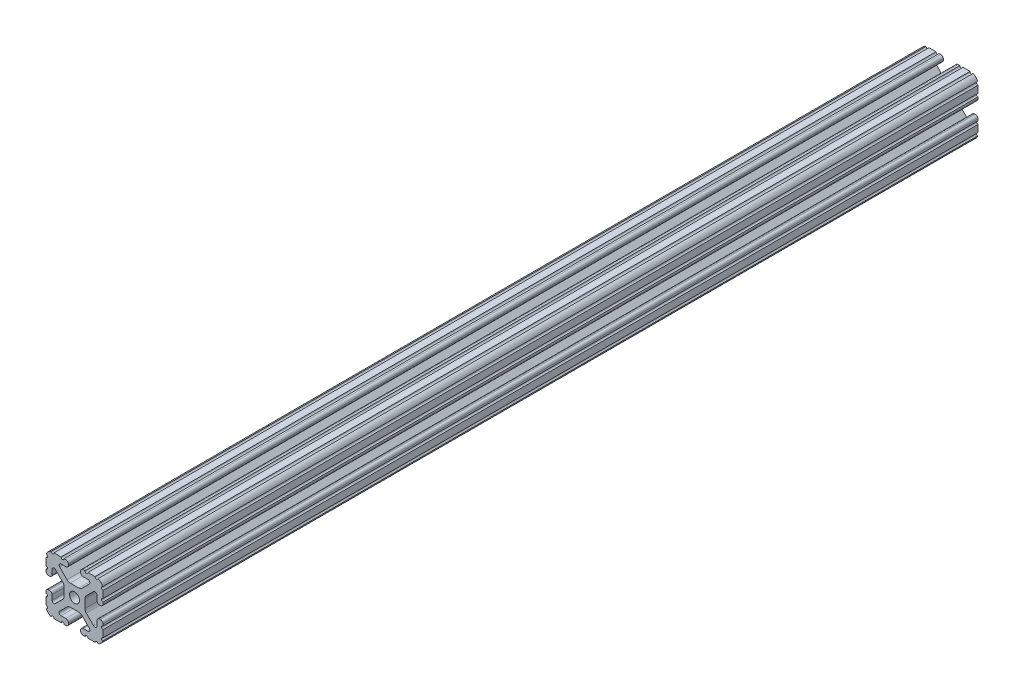
SolidWorks part; units mm, degrees
ref_plane "Front Plane" through (0, 0, 0) normal (0, 0, 1) x (1, 0, 0)
ref_plane "Top Plane" through (0, 0, 0) normal (0, 1, 0) x (1, 0, 0)
ref_plane "Right Plane" through (0, 0, 0) normal (1, 0, 0) x (0, 0, -1)
sketch "Sketch2" plane through (0, 0, 0) normal (0, 0, 1) x (1, 0, 0)
  line L0 (0, 19.05) -> (0, -19.05) construction
  line L1 (-19.05, 0) -> (19.05, 0) construction
  line L2 (4.064, -19.05) -> (19.05, -19.05)
  line L3 (19.05, -19.05) -> (19.05, -4.064)
  line L4 (4.064, -19.05) -> (4.064, -14.986)
  line L5 (4.064, -14.986) -> (12.1123, -14.986)
  line L6 (12.1123, -14.986) -> (4.1113, -6.985)
  line L7 (0, 0) -> (19.05, -19.05) construction
  line L8 (19.05, -4.064) -> (14.986, -4.064)
  line L9 (14.986, -4.064) -> (14.986, -12.1123)
  line L10 (14.986, -12.1123) -> (6.985, -4.1113)
  circle A0 centre (0, 0) radius 3.3274
  arc A1 (8.9963, -14.986) -> (9.909, -12.7826) centre (8.9963, -13.6953) ccw construction
  point P8 (0, -6.985)
  dimension "Center Hole Diameter" = 6.6548
  dimension "Rail Height" = 38.1
  dimension "Rail Width" = 38.1
  dimension "T-Slot Width" = 8.128
  dimension "Slot Inner Width" = 20.574
  dimension "Thickness" = 4.064
  dimension "Slot Depth" = 8.001
  dimension "D1" = 4.064
sketch "Sketch3" plane through (0, 0, 0) normal (1, 0, 0) x (0, 0, -1)
  line L0 (-292.5, -19.05) -> (292.5, -19.05) construction
  line L1 (-267.1, 0) -> (267.1, 0) construction
  dimension "Length" = 585
  dimension "D1" = 25.4
sketch "Sketch4" plane through (0, 0, 0) normal (0, 0, 1) x (1, 0, 0)
  line L0 (5.7912, -19.05) -> (14.3002, -19.05)
  line L1 (4.064, -19.05) -> (19.05, -19.05) construction
  line L2 (4.064, -19.05) -> (4.064, -14.986) construction
  line L3 (4.064, -14.986) -> (12.1123, -14.986) construction
  line L4 (4.064, -16.7132) -> (4.064, -17.3228)
  line L5 (5.7912, -14.986) -> (8.9963, -14.986)
  line L6 (0, -6.985) -> (2.833, -6.985)
  line L7 (12.1123, -14.986) -> (4.1113, -6.985) construction
  line L8 (5.0152, -7.8889) -> (9.909, -12.7826)
  line L9 (19.05, -19.05) -> (19.05, -4.064) construction
  line L10 (14.986, -12.1123) -> (6.985, -4.1113) construction
  line L11 (14.986, -4.064) -> (14.986, -12.1123) construction
  line L12 (14.986, -8.9963) -> (14.986, -5.7912)
  line L13 (19.05, -4.064) -> (14.986, -4.064) construction
  line L14 (16.7132, -4.064) -> (17.3228, -4.064)
  line L15 (19.05, -5.7912) -> (19.05, -14.3002)
  line L16 (12.7826, -9.909) -> (7.8889, -5.0152)
  line L17 (6.985, 0) -> (6.985, -2.833)
  line L18 (-19.05, 0) -> (19.05, 0) construction
  line L19 (0, -6.985) -> (0, -3.3274)
  line L20 (0, 19.05) -> (0, -19.05) construction
  line L21 (6.985, 0) -> (3.3274, 0)
  arc A0 (4.064, -17.3228) -> (5.7912, -19.05) centre (5.7912, -17.3228) ccw
  arc A2 (4.064, -16.7132) -> (5.7912, -14.986) centre (5.7912, -16.7132) cw
  arc A3 (8.9963, -14.986) -> (9.909, -12.7826) centre (8.9963, -13.6953) ccw
  arc A4 (2.833, -6.985) -> (5.0152, -7.8889) centre (2.833, -10.0711) cw
  arc A5 (14.3002, -19.05) -> (19.05, -14.3002) centre (14.3002, -14.3002) ccw
  arc A6 (12.7826, -9.909) -> (14.986, -8.9963) centre (13.6953, -8.9963) ccw
  arc A7 (14.986, -5.7912) -> (16.7132, -4.064) centre (16.7132, -5.7912) cw
  arc A8 (17.3228, -4.064) -> (19.05, -5.7912) centre (17.3228, -5.7912) cw
  arc A9 (7.8889, -5.0152) -> (6.985, -2.833) centre (10.0711, -2.833) cw
  circle A10 centre (0, 0) radius 3.3274 construction
  arc A11 (0, -3.3274) -> (3.3274, 0) centre (0, 0) ccw
  dimension "D1" = 4.7498
  dimension "D2" = 3.0861
  dimension "D3" = 1.7272
extrude "Boss-Extrude1" add sketch "Sketch4" along normal mid plane 585
sketch "Sketch5" plane through (0, 0, 0) normal (0, 0, 1) x (1, 0, 0)
  line L0 (4.064, -19.05) -> (19.05, -19.05) construction
  line L1 (5.7912, -14.986) -> (8.9963, -14.986) construction
  line L3 (0, 0) -> (19.05, -19.05) construction
  line L4 (8.9963, -14.986) -> (8.9963, -19.05) construction
  line L5 (12.1123, -14.986) -> (4.1113, -6.985) construction
  circle A0 centre (14.7395, -19.05) radius 1.016
  circle A1 centre (7.9803, -19.05) radius 1.016
  circle A2 centre (19.05, -14.7395) radius 1.016
  circle A3 centre (19.05, -7.9803) radius 1.016
  point P10 (7.3938, -14.986)
  point P12 (13.6953, -8.9963)
  dimension "D1" = 2.032
extrude "Cut-Extrude1" cut sketch "Sketch5" against normal through all both and the other way through all
mirror "Mirror1" about plane through (0, 0, 0) normal (1, 0, 0) of bodies 137 134
mirror "Mirror2" about plane through (0, 0, 0) normal (0, 1, 0) of bodies 135
equation "\"D1@Boss-Extrude1\"=\"Length@Sketch3\""
equation "\"D1@Sketch2\"=\"Thickness@Sketch2\""
equation "\"D2@Sketch4\"=\"Slot Inner Width@Sketch2\"*0.15"
equation "\"D1@Sketch4\"=\"D3@Sketch4\"*2.75"
equation "\"D3@Sketch4\"=\"Thickness@Sketch2\"*0.425"
equation "\"D1@Sketch5\"=\"Thickness@Sketch2\"*0.5"
